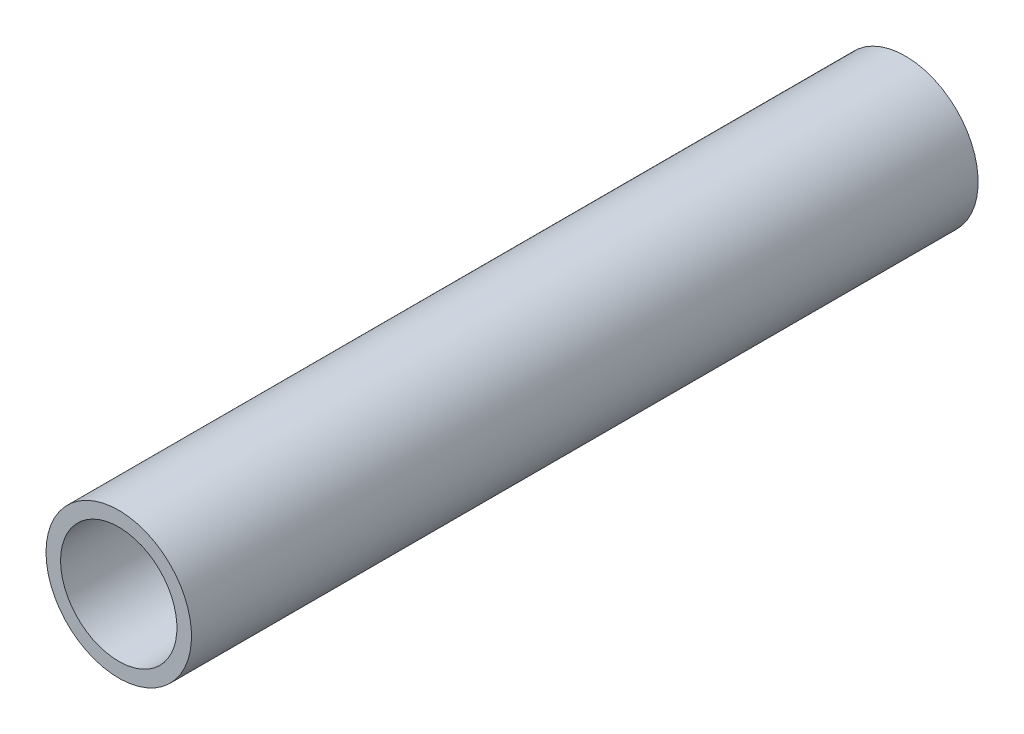
SolidWorks part; units mm, degrees
ref_plane "Front Plane" through (0, 0, 0) normal (0, 0, 1) x (1, 0, 0)
ref_plane "Top Plane" through (0, 0, 0) normal (0, 1, 0) x (1, 0, 0)
ref_plane "Right Plane" through (0, 0, 0) normal (1, 0, 0) x (0, 0, -1)
sketch "Sketch1" plane through (0, 0, 0) normal (0, 0, 1) x (1, 0, 0)
  circle A0 centre (0, 0) radius 1.25
  circle A1 centre (0, 0) radius 1
extrude "Boss-Extrude1" add sketch "Sketch1" along normal blind 13.52
